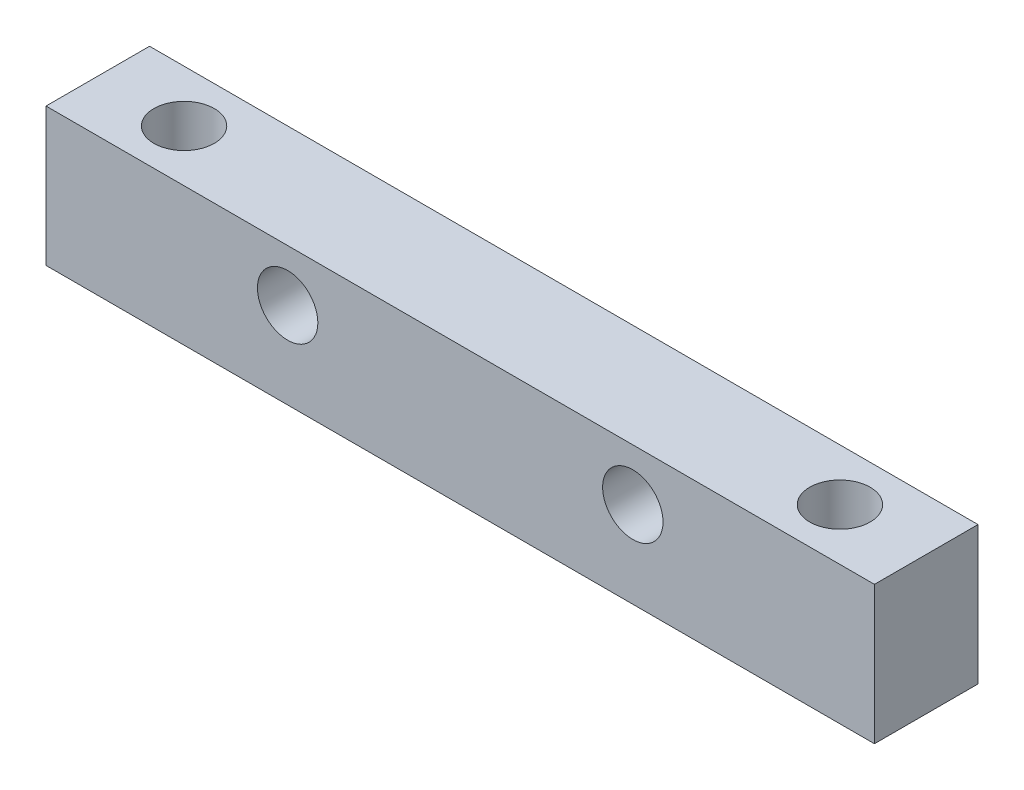
SolidWorks part; units mm, degrees
ref_plane "前视基准面" through (0, 0, 0) normal (0, 0, 1) x (1, 0, 0)
ref_plane "上视基准面" through (0, 0, 0) normal (0, 1, 0) x (1, 0, 0)
ref_plane "右视基准面" through (0, 0, 0) normal (1, 0, 0) x (0, 0, -1)
sketch "草图1" plane through (0, 0, 0) normal (0, 1, 0) x (1, 0, 0)
  line L0 (0, 0) -> (38, 0) construction
  line L2 (-5, -3) -> (43, -3)
  line L3 (-5, -3) -> (-5, 3)
  line L4 (-5, 3) -> (43, 3)
  line L5 (43, -3) -> (43, 3)
  circle A0 centre (0, 0) radius 1.75
  circle A1 centre (38, 0) radius 1.75
  dimension "D2" = 3.5
  dimension "D3" = 3
  dimension "D1" = 38
  dimension "D4" = 3
  dimension "D5" = 5
  dimension "D6" = 5
extrude "凸台-拉伸1" add sketch "草图1" along normal blind 8
sketch "草图2" plane through (0, 0, 3) normal (0, 0, 1) x (1, 0, 0)
  line L0 (9, 5) -> (29, 5) construction
  line L2 (-5, 8) -> (-5, 0) construction
  line L3 (-5, 0) -> (43, 0) construction
  circle A0 centre (9, 5) radius 1.75
  circle A1 centre (29, 5) radius 1.75
  dimension "D2" = 3.5
  dimension "D1" = 20
  dimension "D3" = 5
  dimension "D4" = 14
extrude "切除-拉伸1" cut sketch "草图2" against normal through all
sketch "草图3" plane through (0, 8, 0) normal (0, 1, 0) x (1, 0, 0)
  line L0 (0, 107) -> (0, 0) construction
  line L1 (3, 3) -> (-5, 3)
  line L2 (3, 3) -> (3, 112)
  line L3 (3, 112) -> (-5, 112)
  line L4 (-5, 3) -> (-5, 112)
  circle A0 centre (0, 107) radius 1.75
  circle A1 centre (38, 0) radius 1.75 construction
  dimension "D2" = 5
  dimension "D1" = 8
  dimension "D3" = 107
extrude "凸台-拉伸2" [suppressed] add sketch "草图3" against normal up to surface (8 mm away)
